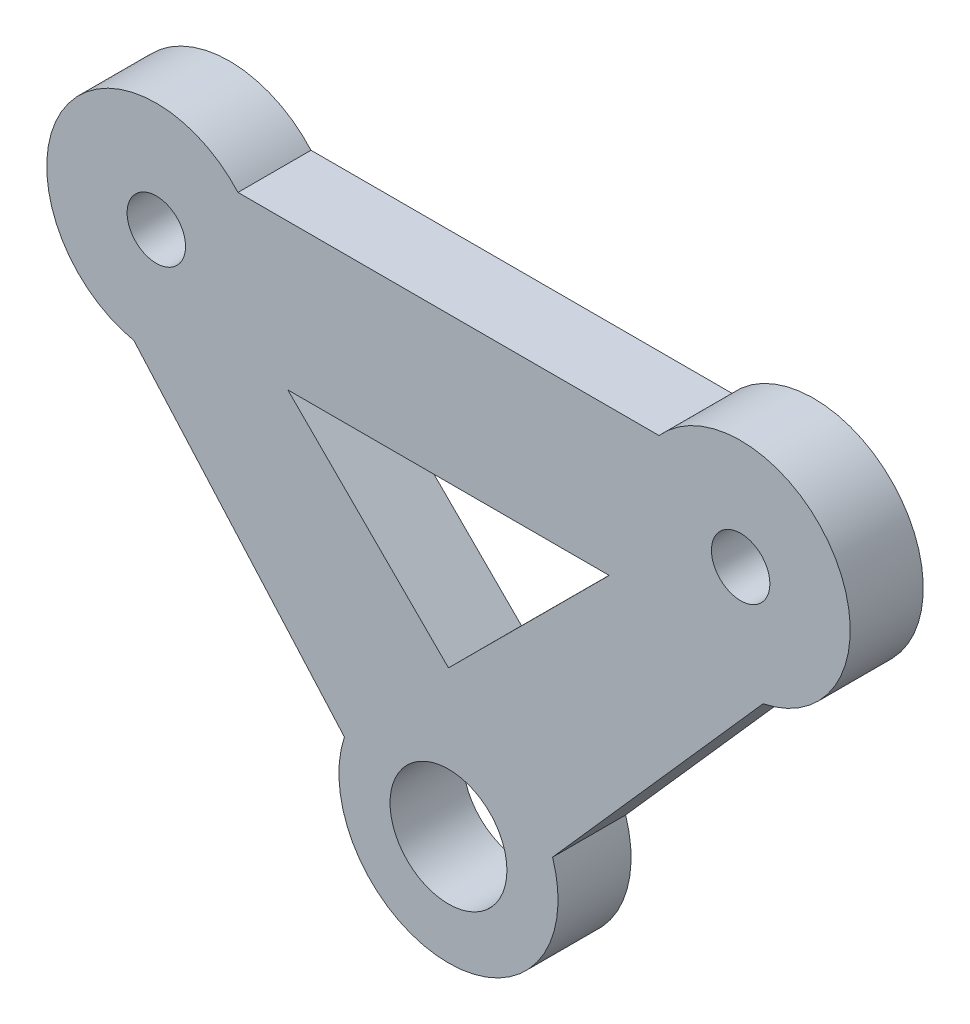
SolidWorks part; units mm, degrees
ref_plane "Piano frontale" through (0, 0, 0) normal (0, 0, 1) x (1, 0, 0)
ref_plane "Piano superiore" through (0, 0, 0) normal (0, 1, 0) x (1, 0, 0)
ref_plane "Piano destro" through (0, 0, 0) normal (1, 0, 0) x (0, 0, -1)
sketch "Schizzo1" plane through (0, 0, 0) normal (0, 0, 1) x (1, 0, 0)
  line L0 (0, -13.1274) -> (0, 49.6661) construction
  line L4 (14.4098, 30.9808) -> (-14.4098, 30.9808)
  line L5 (7.1252, 2.3412) -> (21.535, 18.6395)
  line L6 (11, 20.9808) -> (-11, 20.9808)
  line L7 (-11, 20.9808) -> (0, 10)
  line L8 (0, 10) -> (11, 20.9808)
  line L9 (-21.535, 18.6395) -> (-7.1252, 2.3412)
  circle A0 centre (0, 0) radius 4
  circle A2 centre (20, 25.9808) radius 2
  circle A3 centre (-20, 25.9808) radius 2
  arc A4 (-14.4098, 30.9808) -> (-21.535, 18.6395) centre (-20, 25.9808) ccw
  arc A5 (21.535, 18.6395) -> (14.4098, 30.9808) centre (20, 25.9808) ccw
  arc A6 (-7.1252, 2.3412) -> (7.1252, 2.3412) centre (0, 0) ccw
  dimension "D1" = 8
  dimension "D3" = 4
  dimension "D4" = 4
  dimension "D5" = 15
  dimension "D6" = 15
  dimension "D7" = 15
  dimension "D2" = 40
  dimension "D8" = 22
extrude "Estrusione-Estrusione1" add sketch "Schizzo1" along normal blind 5
